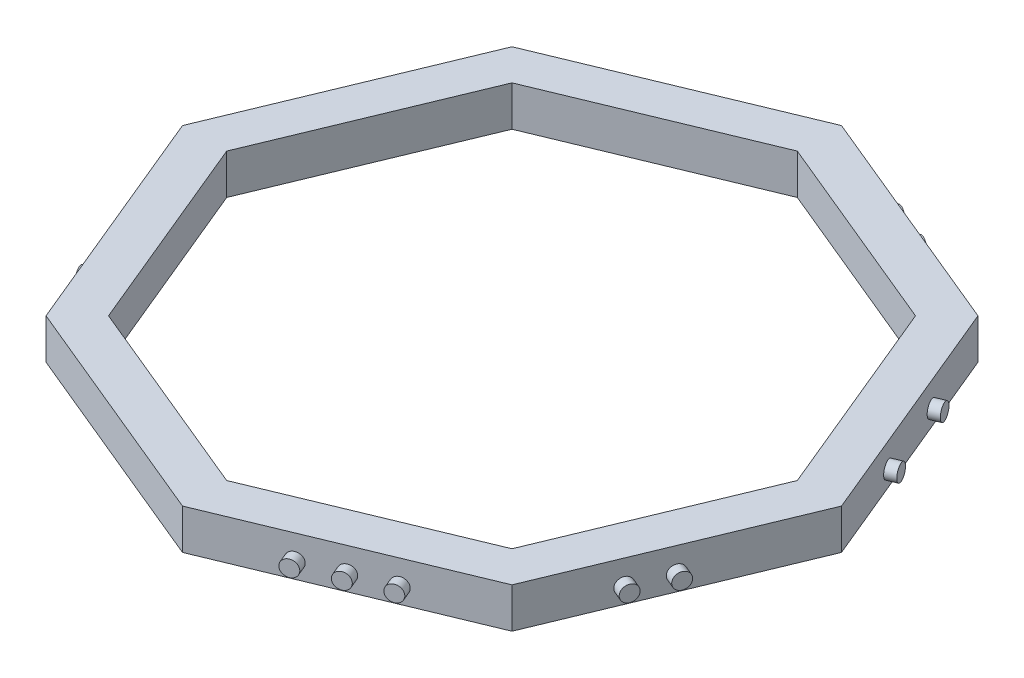
SolidWorks part; units mm, degrees
ref_plane "Front Plane" through (0, 0, 0) normal (0, 0, 1) x (1, 0, 0)
ref_plane "Top Plane" through (0, 0, 0) normal (0, 1, 0) x (1, 0, 0)
ref_plane "Right Plane" through (0, 0, 0) normal (1, 0, 0) x (0, 0, -1)
sketch "Sketch3" plane through (0, 0, 0) normal (0, 1, 0) x (1, 0, 0)
  line L1 (41, 0) -> (28.9914, 28.9914)
  line L2 (28.9914, 28.9914) -> (0, 41)
  line L3 (0, 41) -> (-28.9914, 28.9914)
  line L4 (-28.9914, 28.9914) -> (-41, 0)
  line L5 (-41, 0) -> (-28.9914, -28.9914)
  line L6 (-28.9914, -28.9914) -> (0, -41)
  line L7 (0, -41) -> (28.9914, -28.9914)
  line L8 (28.9914, -28.9914) -> (41, 0)
  circle A0 centre (0, 0) radius 37.8791 construction
  dimension "D1" = 41
extrude "Boss-Extrude1" add sketch "Sketch3" along normal blind 5
sketch "Sketch5" plane through (0, 5, 0) normal (0, 1, 0) x (1, 0, 0)
  line L1 (35.5, 0) -> (25.1023, 25.1023)
  line L2 (25.1023, 25.1023) -> (0, 35.5)
  line L3 (0, 35.5) -> (-25.1023, 25.1023)
  line L4 (-25.1023, 25.1023) -> (-35.5, 0)
  line L5 (-35.5, 0) -> (-25.1023, -25.1023)
  line L6 (-25.1023, -25.1023) -> (0, -35.5)
  line L7 (0, -35.5) -> (25.1023, -25.1023)
  line L8 (25.1023, -25.1023) -> (35.5, 0)
  circle A0 centre (0, 0) radius 32.7977 construction
  dimension "D2" = 41
  dimension "D1" = 35.5
extrude "Cut-Extrude1" cut sketch "Sketch5" against normal blind 5
sketch "Sketch6" plane through (14.4957, 0, 34.9957) normal (0.3827, 0, 0.9239) x (0.9239, 0, -0.3827)
  circle A0 centre (0, 2) radius 1
  circle A1 centre (-5, 2) radius 1
  circle A2 centre (5, 2) radius 1
sketch "Sketch7" plane through (-34.9957, 0, 14.4957) normal (-0.9239, 0, 0.3827) x (0.3827, 0, 0.9239)
  circle A0 centre (5, 2) radius 1
sketch "Sketch8" plane through (-34.9957, 0, -14.4957) normal (-0.9239, 0, -0.3827) x (-0.3827, 0, 0.9239)
  circle A0 centre (0, 2) radius 1
sketch "Sketch9" plane through (-14.4957, 0, -34.9957) normal (-0.3827, 0, -0.9239) x (-0.9239, 0, 0.3827)
  circle A0 centre (-5, 2) radius 1
sketch "Sketch10" plane through (14.4957, 0, -34.9957) normal (0.3827, 0, -0.9239) x (-0.9239, 0, -0.3827)
  circle A0 centre (0, 2) radius 1
  circle A1 centre (5, 2) radius 1
sketch "Sketch11" plane through (34.9957, 0, -14.4957) normal (0.9239, 0, -0.3827) x (-0.3827, 0, -0.9239)
  circle A0 centre (5, 2) radius 1
  circle A1 centre (-5, 2) radius 1
sketch "Sketch12" plane through (34.9957, 0, 14.4957) normal (0.9239, 0, 0.3827) x (0.3827, 0, -0.9239)
  circle A0 centre (0, 2) radius 1
  circle A1 centre (-5, 2) radius 1
extrude "Boss-Extrude5" add sketch "Sketch6" along normal blind 1.25 contours A2 | A1 | A0
extrude "Boss-Extrude6" add sketch "Sketch7" along normal blind 1.25 contours A0
extrude "Boss-Extrude7" add sketch "Sketch8" along normal blind 1.25 contours A0
extrude "Boss-Extrude8" add sketch "Sketch9" along normal blind 1.25 contours A0
extrude "Boss-Extrude9" add sketch "Sketch10" along normal blind 1.25 contours A0 | A1
extrude "Boss-Extrude10" add sketch "Sketch11" along normal blind 1.25 contours A1 | A0
extrude "Boss-Extrude11" add sketch "Sketch12" along normal blind 1.25 contours A1 | A0
